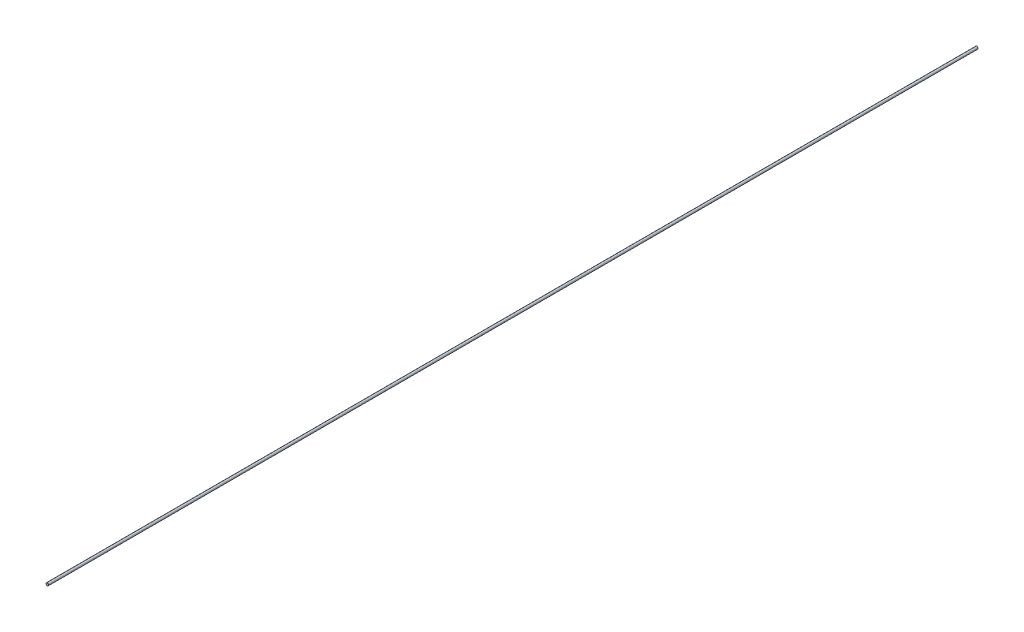
SolidWorks part; units mm, degrees
ref_plane "Front Plane" through (0, 0, 0) normal (0, 0, 1) x (1, 0, 0)
ref_plane "Top Plane" through (0, 0, 0) normal (0, 1, 0) x (1, 0, 0)
ref_plane "Right Plane" through (0, 0, 0) normal (1, 0, 0) x (0, 0, -1)
sketch "Sketch1" plane through (0, 0, 0) normal (0, 0, 1) x (1, 0, 0)
  line L1 (-2.5, 0) -> (2.5, 0) construction
  dimension "OD" = 5
sketch "Sketch2" plane through (0, 0, 0) normal (1, 0, 0) x (0, 0, -1)
  line L0 (914.4, 0) -> (-914.4, 0)
  point P4 (0, 0)
  dimension "Length" = 1828.8
sketch "Sketch3" plane through (0, 0, 0) normal (0, 0, 1) x (1, 0, 0)
  circle A0 centre (0, 0) radius 2.5
extrude "Boss-Extrude1" add sketch "Sketch3" along normal up to vertex (914.4 mm away) and the other way up to vertex (914.4 mm away) up to point (0, 0, 914.4) other way up to point (0, 0, -914.4)
